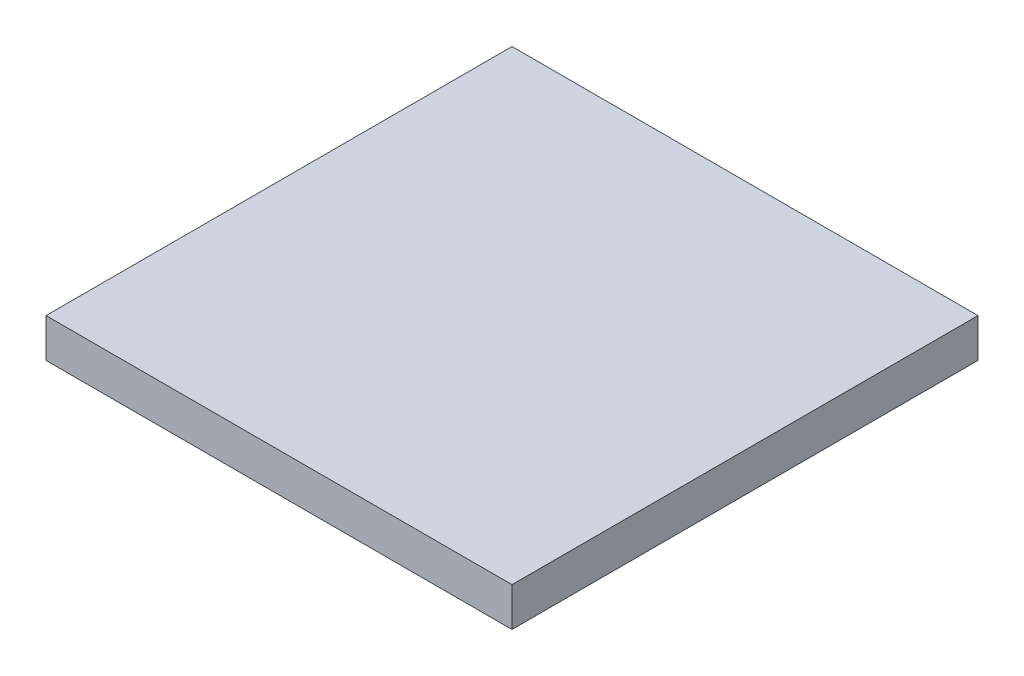
SolidWorks part; units mm, degrees
ref_plane "Front Plane" through (0, 0, 0) normal (0, 0, 1) x (1, 0, 0)
ref_plane "Top Plane" through (0, 0, 0) normal (0, 1, 0) x (1, 0, 0)
ref_plane "Right Plane" through (0, 0, 0) normal (1, 0, 0) x (0, 0, -1)
sketch "Sketch1" plane through (0, 0, 0) normal (0, 1, 0) x (1, 0, 0)
  line L1 (3, -3) -> (-3, -3)
  line L2 (3, -3) -> (3, 3)
  line L3 (3, 3) -> (-3, 3)
  line L4 (-3, -3) -> (-3, 3)
  line L5 (3, -3) -> (-3, 3) construction
  line L6 (3, 3) -> (-3, -3) construction
  point P0 (0, 0)
  dimension "D1" = 6
  dimension "D2" = 6
extrude "Boss-Extrude1" add sketch "Sketch1" along normal blind 0.5
